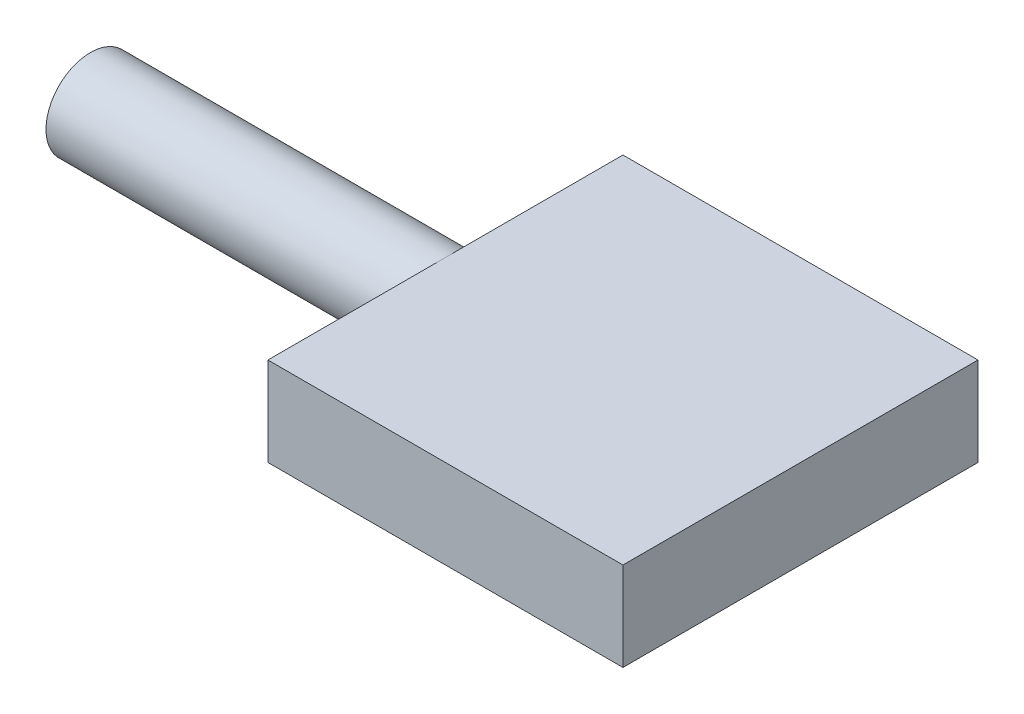
SolidWorks part; units mm, degrees
ref_plane "Alzado" through (0, 0, 0) normal (0, 0, 1) x (1, 0, 0)
ref_plane "Planta" through (0, 0, 0) normal (0, 1, 0) x (1, 0, 0)
ref_plane "Vista lateral" through (0, 0, 0) normal (1, 0, 0) x (0, 0, -1)
sketch "Croquis1" plane through (0, 0, 0) normal (0, 1, 0) x (1, 0, 0)
  line L1 (0, 0) -> (40, 0)
  line L2 (0, 0) -> (0, 40)
  line L3 (0, 40) -> (40, 40)
  line L4 (40, 0) -> (40, 40)
  dimension "D1" = 40
  dimension "D2" = 40
extrude "Saliente-Extruir1" add sketch "Croquis1" along normal blind 10
sketch "Croquis2" plane through (0, 0, 0) normal (-1, 0, 0) x (0, 0, 1)
  line L0 (-20, 0) -> (-20, 10) construction
  line L1 (-40, 0) -> (0, 0) construction
  line L2 (-40, 10) -> (0, 10) construction
  circle A0 centre (-20, 5) radius 5
extrude "Saliente-Extruir2" add sketch "Croquis2" along normal blind 40
